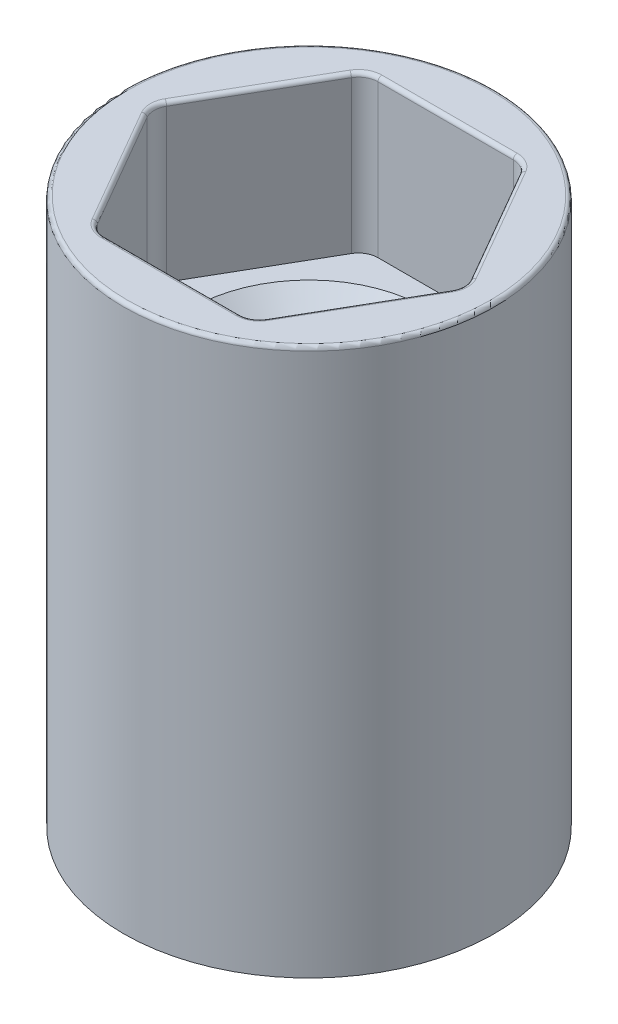
SolidWorks part; units mm, degrees
material "Plain Carbon Steel"
ref_plane "Front Plane" through (0, 0, 0) normal (0, 0, 1) x (1, 0, 0)
ref_plane "Top Plane" through (0, 0, 0) normal (0, 1, 0) x (1, 0, 0)
ref_plane "Right Plane" through (0, 0, 0) normal (1, 0, 0) x (0, 0, -1)
sketch "Sketch1" plane through (0, 0, 0) normal (0, 1, 0) x (1, 0, 0)
  line L1 (3.4641, 0) -> (1.7321, 3) construction
  line L2 (1.7321, 3) -> (-1.7321, 3) construction
  line L3 (-1.7321, 3) -> (-3.4641, 0) construction
  line L4 (-3.4641, 0) -> (-1.7321, -3) construction
  line L5 (-1.7321, -3) -> (1.7321, -3) construction
  line L6 (1.7321, -3) -> (3.4641, 0) construction
  circle A0 centre (0, 0) radius 4.75
  circle A1 centre (0, 0) radius 3 construction
  circle A2 centre (0, 0) radius 3 construction
  circle A3 centre (0, 0) radius 2.5
  dimension "D1" = 9.5
  dimension "D2" = 6
  dimension "D3" = 5
extrude "Boss-Extrude1" add sketch "Sketch1" along normal blind 14
sketch "Sketch2" plane through (0, 14, 0) normal (0, 1, 0) x (1, 0, 0)
  line L1 (4.0415, 0) -> (2.0207, 3.5)
  line L2 (2.0207, 3.5) -> (-2.0207, 3.5)
  line L3 (-2.0207, 3.5) -> (-4.0415, 0)
  line L4 (-4.0415, 0) -> (-2.0207, -3.5)
  line L5 (-2.0207, -3.5) -> (2.0207, -3.5)
  line L6 (2.0207, -3.5) -> (4.0415, 0)
  circle A0 centre (0, 0) radius 3.5 construction
  dimension "D1" = 7
extrude "Cut-Extrude1" cut sketch "Sketch2" against normal blind 4
fillet "Fillet1" radius 0.5 6 edges at (2.0207, 12, 3.5) (-2.0207, 12, 3.5) (-4.0415, 12, 0) (4.0415, 12, 0) (2.0207, 12, -3.5) (-2.0207, 12, -3.5)
chamfer "Chamfer1" distance 0.5 angle 45 2 edges at (0, 10, 2.5) (0, 0, 2.5)
fillet "Fillet2" radius 0.1 13 edges at (0, 14, 4.75) (3.9641, 14, 0) (3.0311, 14, -1.75) (1.9821, 14, -3.433) (0, 14, -3.5) (-1.9821, 14, -3.433) (-3.0311, 14, -1.75) (-3.9641, 14, 0) (-3.0311, 14, 1.75) (-1.9821, 14, 3.433) (0, 14, 3.5) (1.9821, 14, 3.433) (3.0311, 14, 1.75)
